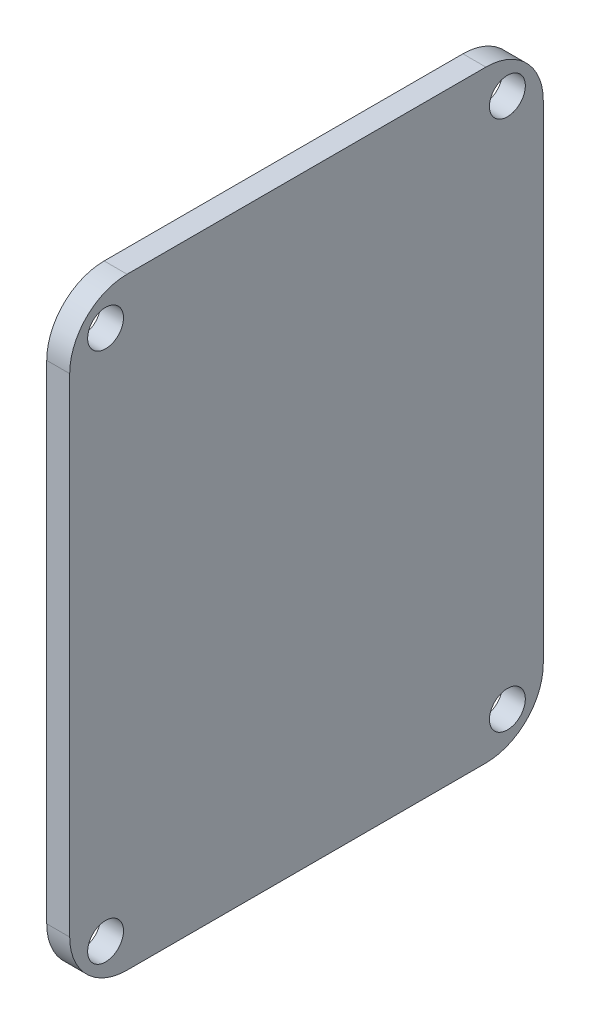
SolidWorks part; units mm, degrees
ref_plane "Front Plane" through (0, 0, 0) normal (1, 0, 0) x (0, 1, 0)
ref_plane "Top Plane" through (0, 0, 0) normal (0, 0, 1) x (0, 1, 0)
ref_plane "Right Plane" through (0, 0, 0) normal (0, 1, 0) x (-1, 0, 0)
sketch "Sketch2" plane through (0, 0, 0) normal (1, 0, 0) x (0, 1, 0)
  line L0 (-18.5, 14) -> (-18.5, -14) construction
  line L1 (-17, -16.5) -> (17, -16.5)
  line L2 (-21, -12.5) -> (-21, 12.5)
  line L3 (-17, 16.5) -> (17, 16.5)
  line L4 (21, -12.5) -> (21, 12.5)
  line L5 (0, 16.5) -> (0, -16.5) construction
  line L6 (-21, 0) -> (21, 0) construction
  line L7 (-18.5, 14) -> (18.5, 14) construction
  line L8 (18.5, 14) -> (18.5, -14) construction
  line L9 (18.5, -14) -> (-18.5, -14) construction
  circle A0 centre (-18.5, 14) radius 1.25
  circle A1 centre (-18.5, -14) radius 1.25
  circle A2 centre (18.5, 14) radius 1.25
  circle A3 centre (18.5, -14) radius 1.25
  arc A4 (-17, -16.5) -> (-21, -12.5) centre (-17, -12.5) cw
  arc A5 (17, -16.5) -> (21, -12.5) centre (17, -12.5) ccw
  arc A6 (17, 16.5) -> (21, 12.5) centre (17, 12.5) cw
  arc A7 (-21, 12.5) -> (-17, 16.5) centre (-17, 12.5) cw
  point P0 (0, 0)
  point P15 (19.8499, -14)
  point P16 (0, 0)
  point P19 (-21, -16.5)
  point P22 (21, -16.5)
  point P25 (21, 16.5)
  dimension "D1" = 2.5
  dimension "D5" = 37
  dimension "D6" = 4
  dimension "D2" = 33
  dimension "D3" = 42
  dimension "D4" = 28
extrude "Boss-Extrude1" add sketch "Sketch2" along normal blind 1.6
